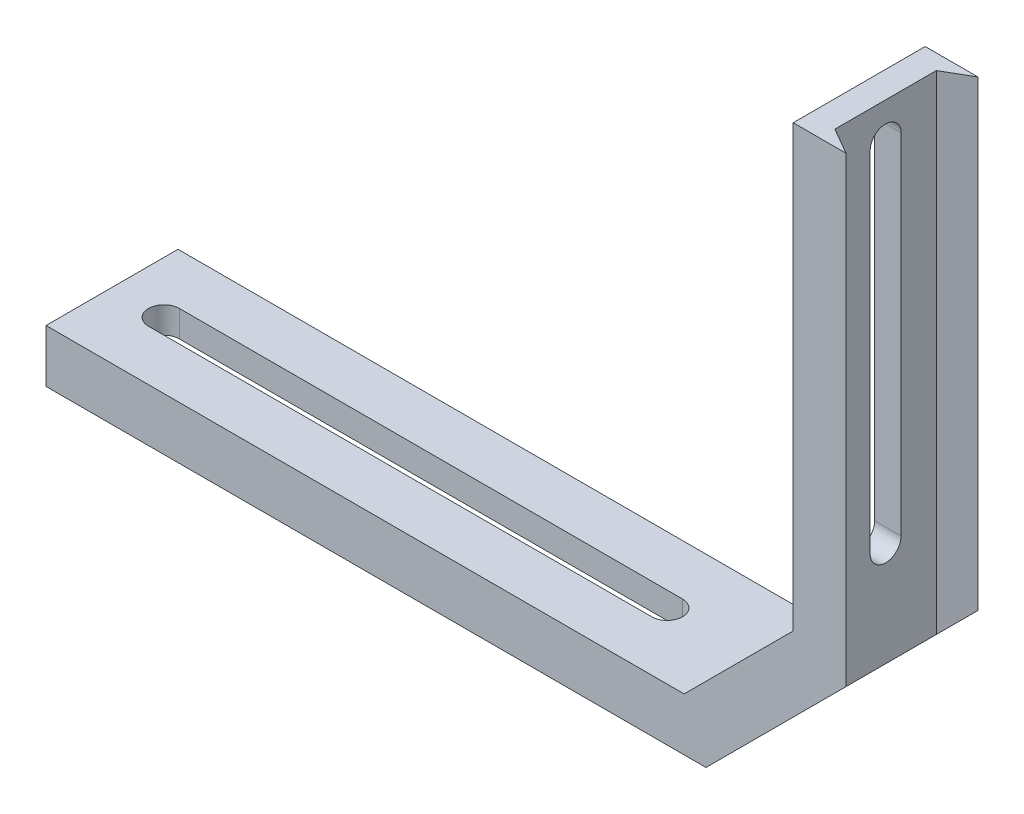
SolidWorks part; units mm, degrees
ref_plane "Спереди" through (0, 0, 0) normal (0, 0, 1) x (1, 0, 0)
ref_plane "Сверху" through (0, 0, 0) normal (0, 1, 0) x (1, 0, 0)
ref_plane "Справа" through (0, 0, 0) normal (1, 0, 0) x (0, 0, -1)
sketch "Эскиз1" plane through (0, 0, 0) normal (0, 0, 1) x (1, 0, 0)
  line L0 (0, 0) -> (0, -8)
  line L1 (0, -8) -> (100, -8)
  line L2 (100, -8) -> (121.2132, 13.2132)
  line L3 (121.2132, 13.2132) -> (121.2132, 83.2132)
  line L4 (121.2132, 83.2132) -> (113.2132, 83.2132)
  line L5 (113.2132, 83.2132) -> (113.2132, 16.5269)
  line L6 (113.2132, 16.5269) -> (96.6863, 0)
  line L7 (96.6863, 0) -> (0, 0)
  dimension "D1" = 100
  dimension "D2" = 135
  dimension "D3" = 8
  dimension "D4" = 8
  dimension "D5" = 70
  dimension "D6" = 8
  dimension "D7" = 30
extrude "Бобышка-Вытянуть1" add sketch "Эскиз1" along normal blind 20
sketch "Эскиз2" plane through (0, 0, 0) normal (-1, 0, 0) x (0, 0, 1)
  line L0 (0, -3) -> (2.8868, -3)
  line L2 (20, -8) -> (0, -8) construction
  line L3 (0, 0) -> (0, -8) construction
  line L4 (2.8868, -3) -> (0, -8)
  line L5 (0, -8) -> (0, -3)
  line L7 (20, -8) -> (20, -3)
  line L8 (20, -3) -> (17.1132, -3)
  line L9 (10, -8) -> (10, -2.4441) construction
  line L10 (17.1132, -3) -> (20, -8)
  dimension "D1" = 60
  dimension "D2" = 5
extrude "Вырез-Вытянуть1" [suppressed] cut sketch "Эскиз2" against normal through all
sketch "Эскиз3" plane through (0, 83.2132, 0) normal (0, 1, 0) x (1, 0, 0)
  line L0 (116.2132, -20) -> (116.2132, -17.1132)
  line L1 (121.2132, -20) -> (113.2132, -20) construction
  line L2 (116.2132, -17.1132) -> (121.2132, -20)
  line L3 (121.2132, -20) -> (116.2132, -20)
  line L4 (121.2132, -10) -> (115.5253, -10) construction
  line L5 (121.2132, -20) -> (121.2132, 0) construction
  line L6 (121.2132, 0) -> (116.2132, 0)
  line L7 (116.2132, 0) -> (116.2132, -2.8868)
  line L8 (116.2132, -2.8868) -> (121.2132, 0)
  dimension "D1" = 5
  dimension "D2" = 60
extrude "Вырез-Вытянуть2" [suppressed] cut sketch "Эскиз3" against normal through all
sketch "Эскиз4" plane through (0, 0, 0) normal (-1, 0, 0) x (0, 0, 1)
  line L0 (0, -8) -> (2.3094, -4)
  line L1 (2.3094, -4) -> (17.6906, -4)
  line L2 (17.6906, -4) -> (20, -8)
  line L3 (20, -8) -> (0, -8)
  dimension "D1" = 4
  dimension "D2" = 60
  dimension "D3" = 60
extrude "Вырез-Вытянуть3" cut sketch "Эскиз4" against normal through all
sketch "Эскиз5" plane through (0, 83.2132, 0) normal (0, 1, 0) x (1, 0, 0)
  line L0 (121.2132, 0) -> (117.2132, -2.3094)
  line L1 (117.2132, -2.3094) -> (117.2132, -17.6906)
  line L2 (117.2132, -17.6906) -> (121.2132, -20)
  line L3 (121.2132, -20) -> (121.2132, 0)
  dimension "D1" = 4
  dimension "D2" = 60
  dimension "D3" = 60
extrude "Вырез-Вытянуть4" cut sketch "Эскиз5" against normal through all
sketch "Эскиз6" plane through (0, 0, 0) normal (0, 1, 0) x (1, 0, 0)
  line L0 (7.87, -10) -> (84.1044, -10) construction
  line L1 (7.87, -7.6636) -> (84.1044, -7.6636)
  line L2 (7.87, -12.3364) -> (84.1044, -12.3364)
  arc A0 (7.87, -7.6636) -> (7.87, -12.3364) centre (7.87, -10) ccw
  arc A1 (84.1044, -12.3364) -> (84.1044, -7.6636) centre (84.1044, -10) ccw
  point P2 (45.9872, -10)
extrude "Вырез-Вытянуть5" cut sketch "Эскиз6" against normal through all
sketch "Эскиз7" plane through (113.2132, 0, 0) normal (-1, 0, 0) x (0, 0, 1)
  line L0 (10, 77.7165) -> (10, 24.8) construction
  line L1 (12.3403, 77.7165) -> (12.3403, 24.8)
  line L2 (7.6597, 77.7165) -> (7.6597, 24.8)
  arc A0 (12.3403, 77.7165) -> (7.6597, 77.7165) centre (10, 77.7165) ccw
  arc A1 (7.6597, 24.8) -> (12.3403, 24.8) centre (10, 24.8) ccw
  point P2 (10, 51.2583)
extrude "Вырез-Вытянуть6" cut sketch "Эскиз7" against normal through all
